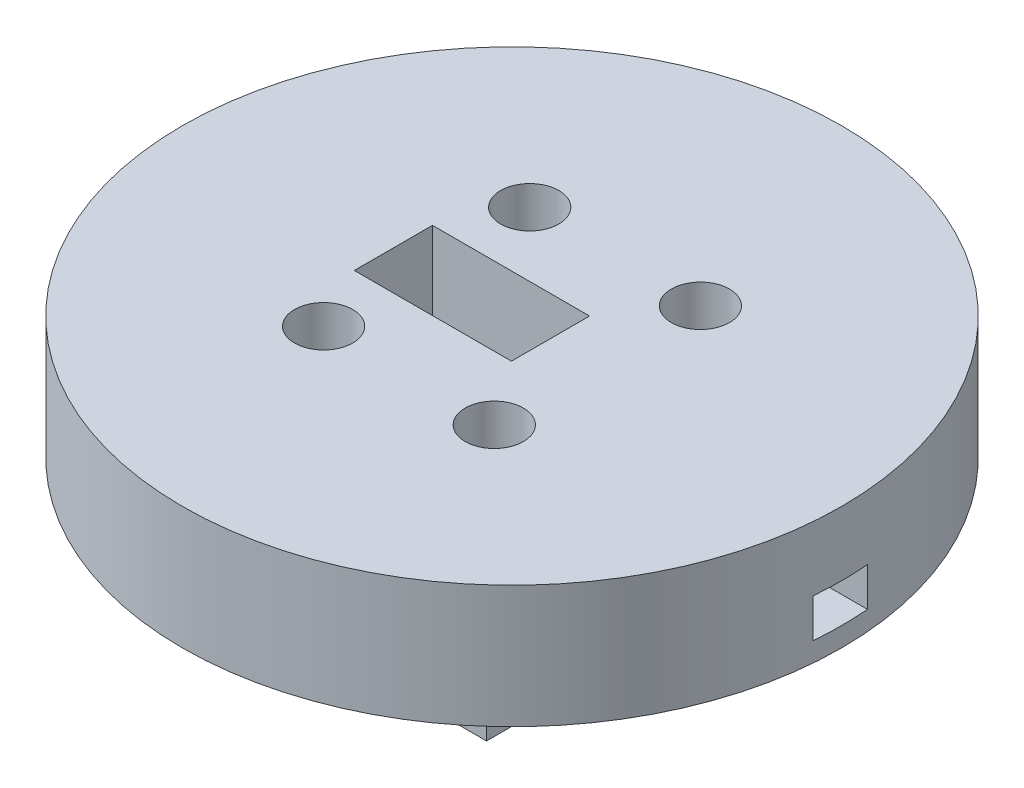
SolidWorks part; units mm, degrees
ref_plane "Ön Düzlem" through (0, 0, 0) normal (0, 0, 1) x (1, 0, 0)
ref_plane "Üst Düzlem" through (0, 0, 0) normal (0, 1, 0) x (1, 0, 0)
ref_plane "Sağ Düzlem" through (0, 0, 0) normal (1, 0, 0) x (0, 0, -1)
sketch "Sketch1" plane through (0, 0, 0) normal (0, 0, 1) x (1, 0, 0)
  line L1 (30, -15) -> (-30, -15)
  line L2 (30, -15) -> (30, 15)
  line L3 (30, 15) -> (-30, 15)
  line L4 (-30, -15) -> (-30, 15)
  line L5 (30, -15) -> (-30, 15) construction
  line L6 (30, 15) -> (-30, -15) construction
  point P0 (0, 0)
  dimension "D1" = 60
  dimension "30" = 30
extrude "Boss-Extrude1" add sketch "Sketch1" along normal mid plane 73.14
sketch "Sketch2" plane through (30, 0, 0) normal (1, 0, 0) x (0, 0, -1)
  line L0 (-36.57, -15) -> (36.57, -15) construction
  line L1 (-6, -15) -> (6, -15)
  line L2 (6, -15) -> (5.8249, -15.1366)
  arc A0 (-6, -15) -> (6, -15) centre (0, -15) cw
  line M4 (-36.57, -15) -> (36.57, -15)
  dimension "D1" = 6
extrude "Cut-Extrude1" cut sketch "Sketch2" against normal up to surface (60 mm away) contours A0 M4 up to face at (-30, 0, 0)
sketch "Sketch3" plane through (0, 0, 36.57) normal (0, 0, 1) x (1, 0, 0)
  line L0 (6.075, 0) -> (11.075, 0)
  line L1 (-30, -15) -> (30, -15) construction
  line L2 (-6.075, 0) -> (-11.075, 0)
  line L3 (-15.0942, -15) -> (15.0942, -15)
  line L4 (0, 13.385) -> (0, -19.9591) construction
  line L5 (30, -15) -> (30, 15) construction
  line L6 (11.075, 0) -> (15.0942, -15)
  line L7 (-11.075, 0) -> (-15.0942, -15)
  arc A0 (6.075, 0) -> (-6.075, 0) centre (0, 0) ccw
  dimension "D4" = 15
  dimension "12" = 12.15
  dimension "D1" = 5
  dimension "D3" = 75
  dimension "D5" = 30
  dimension "D6" = 5
  dimension "D7" = 75
extrude "Cut-Extrude2" cut sketch "Sketch3" against normal up to surface (73.14 mm away) up to face at (0, 0, -36.57)
sketch "Sketch4" plane through (0, 0, 36.57) normal (0, 0, 1) x (1, 0, 0)
  line L0 (30, 15) -> (30, -5)
  line L2 (30, -15) -> (30, 15) construction
  line L3 (30, -5) -> (10, 15)
  line L4 (30, 15) -> (-30, 15) construction
  line L5 (10, 15) -> (30, 15)
  line L6 (0, 20.3589) -> (0, -23.7913) construction
  line L7 (-30, 15) -> (-30, -5)
  line L8 (-10, 15) -> (-30, 15)
  line L9 (-30, -5) -> (-10, 15)
  dimension "D1" = 20
  dimension "20" = 20
extrude "Cut-Extrude3" cut sketch "Sketch4" against normal up to surface (73.14 mm away) up to face at (0, -2.3925, -36.57)
ref_plane "Plane1" through (0, 15, 0) normal (0, 1, 0) x (1, 0, 0)
sketch "Sketch5" plane through (0, 15, 0) normal (0, 1, 0) x (1, 0, 0)
  line L0 (0, -43.2701) -> (0, 38.8321) construction
  line L1 (-54.9807, 0) -> (44.2894, 0) construction
  line L2 (10, -36.57) -> (30, -36.57) construction
  line L3 (30, 36.57) -> (30, -36.57) construction
  circle A0 centre (22, -26.57) radius 3.75
  circle A1 centre (-22, -26.57) radius 3.75
  circle A2 centre (22, 26.57) radius 3.75
  circle A3 centre (-22, 26.57) radius 3.75
  dimension "D3" = 7.5
  dimension "D1" = 10
  dimension "D2" = 8
extrude "Cut-Extrude4" cut sketch "Sketch5" against normal up to surface (30 mm away) up to face at (22.5471, -15, 21.285)
sketch "Sketch6" plane through (0, 15, 0) normal (0, 1, 0) x (1, 0, 0)
  line L0 (0, 39.416) -> (0, -38.5985) construction
  line L1 (-43.185, 0) -> (47.2091, 0) construction
  circle A0 centre (22, -26.57) radius 7.5
  circle A1 centre (-22, -26.57) radius 7.5
  circle A2 centre (22, 26.57) radius 7.5
  circle A3 centre (-22, 26.57) radius 7.5
  dimension "1" = 15
extrude "Cut-Extrude5" cut sketch "Sketch6" against normal blind 20
sketch "Sketch8" plane through (0, 15, 0) normal (0, 1, 0) x (1, 0, 0)
  circle A0 centre (0, 0) radius 85
  dimension "D1" = 170
extrude "Boss-Extrude3" add sketch "Sketch8" along normal blind 31.6
sketch "Sketch9" plane through (0, 15, 0) normal (0, -1, 0) x (1, 0, 0)
  circle A0 centre (22, 26.57) radius 7.5
  circle A1 centre (22, -26.57) radius 7.5
  circle A2 centre (-22, -26.57) radius 7.5
  circle A3 centre (-22, 26.57) radius 7.5
  dimension "D1" = 15
extrude "Cut-Extrude6" cut sketch "Sketch9" against normal up to surface (31.6 mm away) up to face at (-85, 46.6, 0)
sketch "Sketch11" plane through (0, 46.6, 0) normal (0, 1, 0) x (1, 0, 0)
  line L0 (-30, 36.57) -> (-15.0942, 36.57) construction
  line L1 (10, 10) -> (-30.5, 10)
  line L2 (10, 10) -> (10, -10.15)
  line L3 (10, -10.15) -> (-30.5, -10.15)
  line L4 (-30.5, 10) -> (-30.5, -10.15)
  line L6 (30, 36.57) -> (30, -36.57) construction
  dimension "D1" = 26.57
  dimension "D2" = 20.15
  dimension "D3" = 20
  dimension "D4" = 40.5
extrude "Cut-Extrude7" cut sketch "Sketch11" against normal blind 26.6
sketch "Sketch12" plane through (0, 0, 36.57) normal (0, 0, 1) x (1, 0, 0)
  line L0 (30, -5) -> (30, 15)
  line L1 (40.227, 15) -> (-40.227, 15) construction
  line L2 (10, 15) -> (30, 15)
  line L4 (10, 15) -> (30, -5)
  line L5 (-10, 15) -> (-30, -5)
  line L6 (-30, -5) -> (-30, 15)
  line L7 (-30, 15) -> (-10, 15)
extrude "Boss-Extrude4" add sketch "Sketch12" against normal up to surface (73.14 mm away) up to face at (0, -2.8271, -36.57)
sketch "Sketch13" plane through (0, 46.6, 0) normal (0, 1, 0) x (1, 0, 0)
  circle A0 centre (22, 26.57) radius 7.5
  circle A1 centre (-22, 26.57) radius 7.5
  circle A2 centre (-22, -26.57) radius 7.5
  circle A3 centre (22, -26.57) radius 7.5
  dimension "D1" = 15
extrude "Cut-Extrude8" cut sketch "Sketch13" against normal blind 51.6
fillet "Fillet1" radius 8 4 edges at (0, 15, -36.57) (30, 15, 0) (0, 15, 36.57) (-30, 15, 0)
sketch "Sketch14" plane through (10, 0, 0) normal (-1, 0, 0) x (0, 0, 1)
  line L0 (-6.925, 20) -> (-6.925, 30)
  line L1 (10.15, 20) -> (-10, 20) construction
  line L2 (-6.925, 30) -> (7.075, 30)
  line L3 (7.075, 30) -> (7.075, 20)
  line L4 (7.075, 20) -> (-6.925, 20)
  line L5 (10.15, 20) -> (10.15, 46.6) construction
  dimension "D1" = 10
  dimension "D2" = 14
  dimension "D3" = 3.075
extrude "Cut-Extrude9" cut sketch "Sketch14" against normal blind 84
